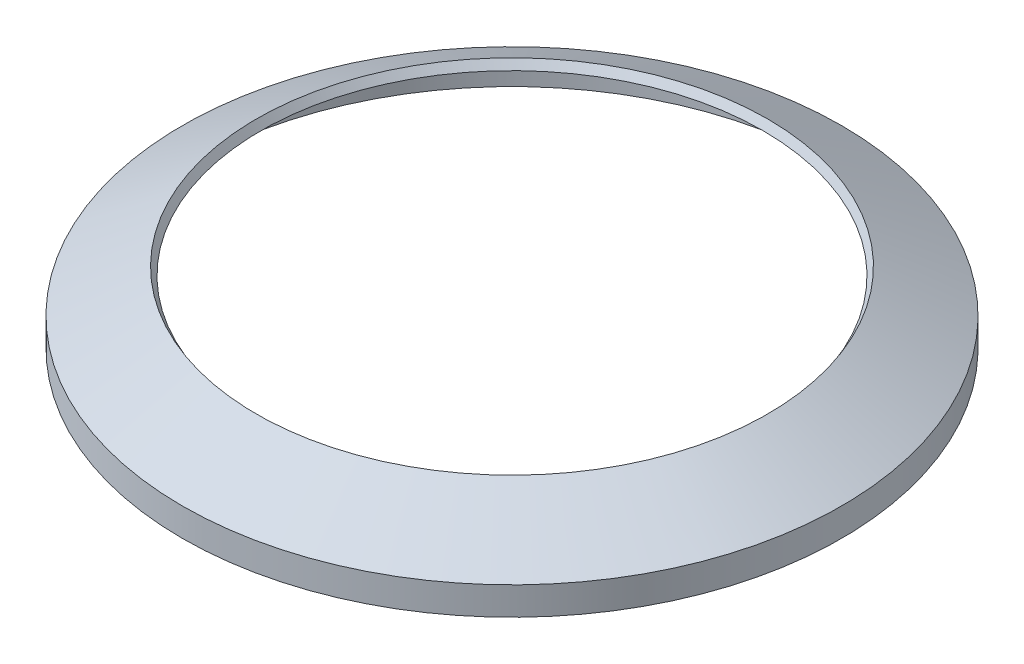
SolidWorks part; units mm, degrees
ref_plane "Front Plane" through (0, 0, 0) normal (0, 0, 1) x (1, 0, 0)
ref_plane "Top Plane" through (0, 0, 0) normal (0, 1, 0) x (1, 0, 0)
ref_plane "Right Plane" through (0, 0, 0) normal (1, 0, 0) x (0, 0, -1)
sketch "Sketch1" plane through (0, 0, 0) normal (0, 0, 1) x (1, 0, 0)
  line L0 (-44.577, 0) -> (-34.925, 5.5726)
  line L1 (-44.577, 0) -> (44.577, 0) construction
  line L2 (0, 0) -> (0, 5.5726) construction
  line L3 (-34.925, 5.5726) -> (34.925, 5.5726) construction
  line L4 (-44.577, 0) -> (-44.577, -3.175)
  dimension "D1" = 89.154
  dimension "D2" = 30
  dimension "D3" = 69.85
  dimension "D4" = 3.175
revolve "Revolve-Thin1" add sketch "Sketch1" angle 360 about L2 wall 1.27
